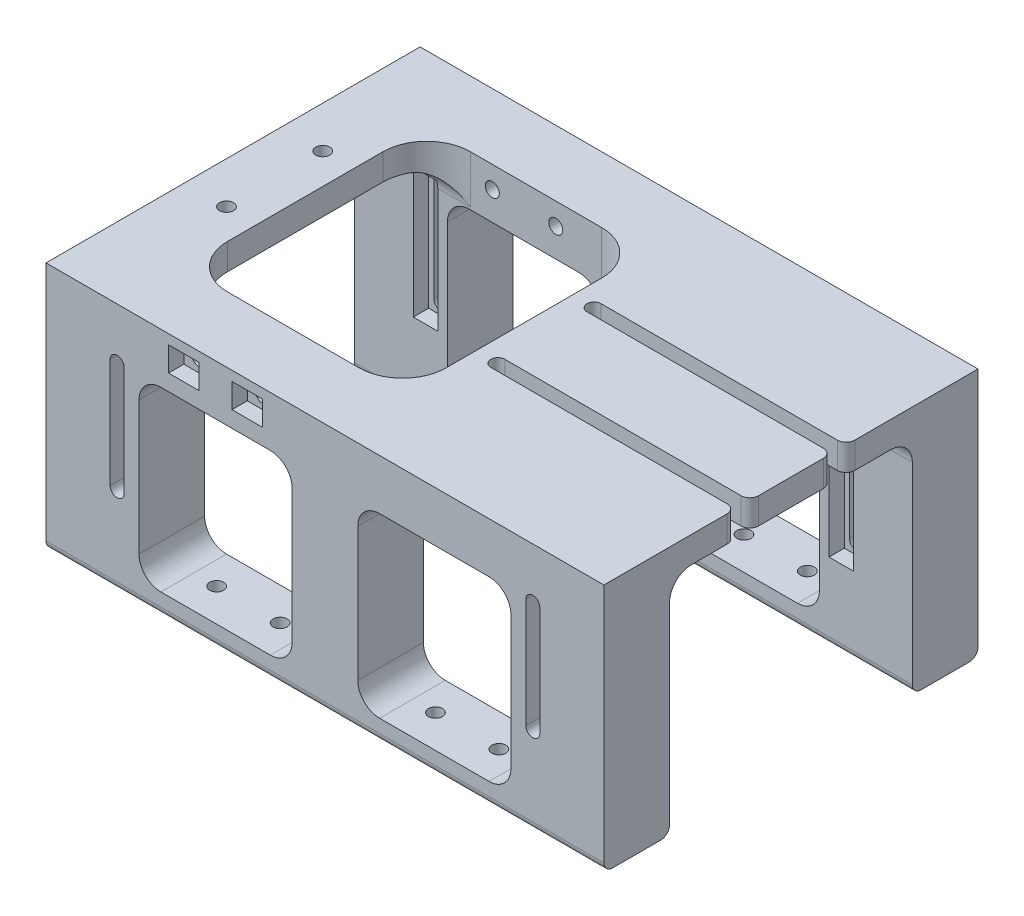
SolidWorks part; units mm, degrees
material "Polyetheretherketone (PEEK)"
ref_plane "Front Plane" through (0, 0, 0) normal (0, 0, 1) x (1, 0, 0)
ref_plane "Top Plane" through (0, 0, 0) normal (0, 1, 0) x (1, 0, 0)
ref_plane "Right Plane" through (0, 0, 0) normal (1, 0, 0) x (0, 0, -1)
sketch "Sketch1" plane through (0, 0, 0) normal (0, 1, 0) x (1, 0, 0)
  line L0 (0, 57.75) -> (0, 85.5)
  line L1 (0, 0) -> (127.5, 0)
  line L2 (0, 0) -> (0, 27.75)
  line L3 (0, 85.5) -> (127.5, 85.5)
  line L4 (127.5, 0) -> (127.5, 28.15)
  line L6 (0, 27.75) -> (0, 57.75)
  line L9 (26.5, 15) -> (56.5, 15)
  line L10 (16.5, 25) -> (16.5, 60.5)
  line L11 (26.5, 70.5) -> (56.5, 70.5)
  line L12 (66.5, 25) -> (66.5, 60.5)
  line L13 (91.5, 53.75) -> (71.5, 53.75) construction
  line L14 (127.5, 57.35) -> (127.5, 85.5)
  line L15 (125.5, 52.15) -> (71.5, 52.15)
  line L16 (125.5, 55.35) -> (71.5, 55.35)
  line L17 (71.5, 31.75) -> (114.75, 31.75) construction
  line L18 (71.5, 33.35) -> (125.5, 33.35)
  line L19 (71.5, 30.15) -> (125.5, 30.15)
  line L20 (127.5, 35.35) -> (127.5, 50.15)
  circle A2 centre (9.5, 53.75) radius 1.6
  circle A3 centre (9.5, 31.75) radius 1.6
  arc A4 (16.5, 60.5) -> (26.5, 70.5) centre (26.5, 60.5) cw
  arc A5 (56.5, 70.5) -> (66.5, 60.5) centre (56.5, 60.5) cw
  arc A6 (56.5, 15) -> (66.5, 25) centre (56.5, 25) ccw
  arc A7 (26.5, 15) -> (16.5, 25) centre (26.5, 25) cw
  arc A11 (71.5, 55.35) -> (71.5, 52.15) centre (71.5, 53.75) ccw
  arc A12 (71.5, 33.35) -> (71.5, 30.15) centre (71.5, 31.75) ccw
  arc A14 (127.5, 28.15) -> (125.5, 30.15) centre (125.5, 28.15) ccw
  arc A15 (127.5, 35.35) -> (125.5, 33.35) centre (125.5, 35.35) cw
  arc A16 (127.5, 50.15) -> (125.5, 52.15) centre (125.5, 50.15) ccw
  arc A17 (127.5, 57.35) -> (125.5, 55.35) centre (125.5, 57.35) cw
  point P19 (125, 53.75)
  point P37 (125, 31.75)
  point P45 (127.5, 33.35)
  point P50 (127.5, 55.35)
  dimension "D1" = 10
  dimension "D2" = 10
  dimension "D3" = 10
  dimension "D4" = 10
  dimension "D5" = 2
extrude "Boss-Extrude1" add sketch "Sketch1" along normal blind 60
sketch "Sketch2" plane through (0, 0, 0) normal (-1, 0, 0) x (0, 0, 1)
  line L0 (-70.5, 8) -> (-70.5, 3)
  line L1 (-65.5, 54) -> (-20, 54)
  line L2 (-70.5, 49) -> (-70.5, 8)
  line L3 (-65.5, 3) -> (-20, 3)
  line L4 (-15, 49) -> (-15, 8)
  line L5 (-70.5, 3) -> (-65.5, 3)
  line L6 (-20, 3) -> (-15, 3)
  line L7 (-15, 8) -> (-15, 3)
  arc A2 (-15, 49) -> (-20, 54) centre (-20, 49) ccw
  arc A3 (-65.5, 54) -> (-70.5, 49) centre (-65.5, 49) ccw
extrude "Cut-Extrude1" cut sketch "Sketch2" against normal through all
sketch "Sketch4" plane through (0, 0, -85.5) normal (0, 0, -1) x (-1, 0, 0)
  line L0 (-56.25, 43.5) -> (-56.25, 13)
  line L1 (-101.25, 48.5) -> (-76.25, 48.5)
  line L2 (-106.25, 43.5) -> (-106.25, 13)
  line L3 (-101.25, 8) -> (-76.25, 8)
  line L4 (-21.25, 43.5) -> (-21.25, 13)
  line L5 (-71.25, 43.5) -> (-71.25, 13)
  line L7 (-51.25, 48.5) -> (-26.25, 48.5)
  line L8 (-51.25, 8) -> (-26.25, 8)
  line L9 (-111.25, 23.25) -> (-111.25, 48.25) construction
  line L10 (-112.85, 23.25) -> (-112.85, 48.25)
  line L11 (-109.65, 23.25) -> (-109.65, 48.25)
  line L12 (-16.25, 23.25) -> (-16.25, 48.25) construction
  line L13 (-17.85, 23.25) -> (-17.85, 48.25)
  line L14 (-14.65, 23.25) -> (-14.65, 48.25)
  arc A0 (-101.25, 48.5) -> (-106.25, 43.5) centre (-101.25, 43.5) ccw
  arc A1 (-51.25, 8) -> (-56.25, 13) centre (-51.25, 13) cw
  arc A2 (-101.25, 8) -> (-106.25, 13) centre (-101.25, 13) cw
  arc A3 (-76.25, 8) -> (-71.25, 13) centre (-76.25, 13) ccw
  arc A4 (-71.25, 43.5) -> (-76.25, 48.5) centre (-76.25, 43.5) ccw
  arc A5 (-26.25, 8) -> (-21.25, 13) centre (-26.25, 13) ccw
  arc A6 (-21.25, 43.5) -> (-26.25, 48.5) centre (-26.25, 43.5) ccw
  arc A7 (-51.25, 48.5) -> (-56.25, 43.5) centre (-51.25, 43.5) ccw
  arc A14 (-112.85, 23.25) -> (-109.65, 23.25) centre (-111.25, 23.25) ccw
  arc A15 (-109.65, 48.25) -> (-112.85, 48.25) centre (-111.25, 48.25) ccw
  arc A16 (-17.85, 23.25) -> (-14.65, 23.25) centre (-16.25, 23.25) ccw
  arc A17 (-14.65, 48.25) -> (-17.85, 48.25) centre (-16.25, 48.25) ccw
  circle A18 centre (-46, 55) radius 1.6
  circle A19 centre (-31.5, 55) radius 1.6
  point P14 (-56.25, 8)
  point P27 (-56.25, 48.5)
  point P38 (-111.25, 35.75)
  point P45 (-16.25, 35.75)
  dimension "D1" = 5
extrude "Cut-Extrude2" cut sketch "Sketch4" against normal through all
ref_plane "Plane1" through (0, 0, -42.75) normal (0, 0, 1) x (1, 0, 0)
sketch "Sketch5" plane through (0, 0, -42.75) normal (0, 0, 1) x (1, 0, 0)
  line L7 (13.45, 50.75) -> (19.05, 50.75)
  line L8 (13.45, 50.75) -> (13.45, 20.75)
  line L9 (13.45, 20.75) -> (19.05, 20.75)
  line L10 (19.05, 50.75) -> (19.05, 20.75)
  line L11 (13.45, 50.75) -> (19.05, 20.75) construction
  line L12 (13.45, 20.75) -> (19.05, 50.75) construction
  line L26 (108.45, 50.75) -> (114.05, 50.75)
  line L27 (108.45, 50.75) -> (108.45, 20.75)
  line L28 (108.45, 20.75) -> (114.05, 20.75)
  line L29 (114.05, 50.75) -> (114.05, 20.75)
  line L30 (108.45, 50.75) -> (114.05, 20.75) construction
  line L31 (108.45, 20.75) -> (114.05, 50.75) construction
  point P6 (16.25, 35.75)
  point P24 (111.25, 35.75)
extrude "Cut-Extrude3" cut sketch "Sketch5" against normal blind 31.25 and the other way blind 31.25
ref_plane "Plane3" through (0, 3, 0) normal (0, 1, 0) x (1, 0, 0)
other "SurfaceCut1"
sketch "Sketch8" plane through (0, 3, 0) normal (0, -1, 0) x (1, 0, 0)
  line L0 (66.5, -42.75) -> (16.5, -42.75) construction
  line L1 (66.5, -25) -> (66.5, -60.5) construction
  line L2 (16.5, -60.5) -> (16.5, -25) construction
  circle A0 centre (31.5, -7.5) radius 1.6
  circle A1 centre (46, -7.5) radius 1.6
  circle A2 centre (31.5, -78) radius 1.6
  circle A3 centre (46, -78) radius 1.6
  circle A4 centre (81.5, -7.5) radius 1.6
  circle A5 centre (96, -7.5) radius 1.6
  circle A6 centre (81.5, -78) radius 1.6
  circle A7 centre (96, -78) radius 1.6
extrude "Cut-Extrude6" cut sketch "Sketch8" against normal up to surface (5 mm away) up to face at (38.75, 8, -78)
fillet "Fillet1" radius 2 1 edges at (63.75, 3, 0)
fillet "Fillet2" radius 2 1 edges at (63.75, 3, -15)
fillet "Fillet3" radius 2 1 edges at (63.75, 3, -70.5)
fillet "Fillet4" radius 2 1 edges at (63.75, 3, -85.5)
sketch "Sketch9" plane through (0, 0, -85.5) normal (0, 0, -1) x (-1, 0, 0)
  line L1 (-49.5, 57.8) -> (-42.5, 57.8)
  line L2 (-49.5, 57.8) -> (-49.5, 52.2)
  line L3 (-49.5, 52.2) -> (-42.5, 52.2)
  line L4 (-42.5, 57.8) -> (-42.5, 52.2)
  line L5 (-49.5, 57.8) -> (-42.5, 52.2) construction
  line L6 (-49.5, 52.2) -> (-42.5, 57.8) construction
  line L7 (-35, 57.8) -> (-28, 57.8)
  line L8 (-35, 57.8) -> (-35, 52.2)
  line L9 (-35, 52.2) -> (-28, 52.2)
  line L10 (-28, 57.8) -> (-28, 52.2)
  line L11 (-35, 57.8) -> (-28, 52.2) construction
  line L12 (-35, 52.2) -> (-28, 57.8) construction
  point P0 (-46, 55)
  point P6 (-31.5, 55)
sketch "Sketch10" plane through (0, 0, 0) normal (0, 0, 1) x (1, 0, 0)
  line L0 (35, 52.2) -> (28, 57.8) construction
  line L1 (28, 52.2) -> (35, 52.2)
  line L2 (28, 52.2) -> (28, 57.8)
  line L3 (28, 57.8) -> (35, 57.8)
  line L4 (35, 52.2) -> (35, 57.8)
  line L5 (28, 52.2) -> (35, 57.8) construction
  line L6 (28, 57.8) -> (35, 52.2) construction
  line L7 (49.5, 52.2) -> (42.5, 57.8) construction
  line L8 (42.5, 52.2) -> (49.5, 52.2)
  line L9 (42.5, 52.2) -> (42.5, 57.8)
  line L10 (42.5, 57.8) -> (49.5, 57.8)
  line L11 (49.5, 52.2) -> (49.5, 57.8)
  line L12 (42.5, 52.2) -> (49.5, 57.8) construction
  line L13 (42.5, 57.8) -> (49.5, 52.2) construction
  point P0 (31.5, 55)
  point P8 (46, 55)
extrude "Cut-Extrude7" cut sketch "Sketch9" against normal blind 3.5
extrude "Cut-Extrude8" cut sketch "Sketch10" against normal blind 3.5
